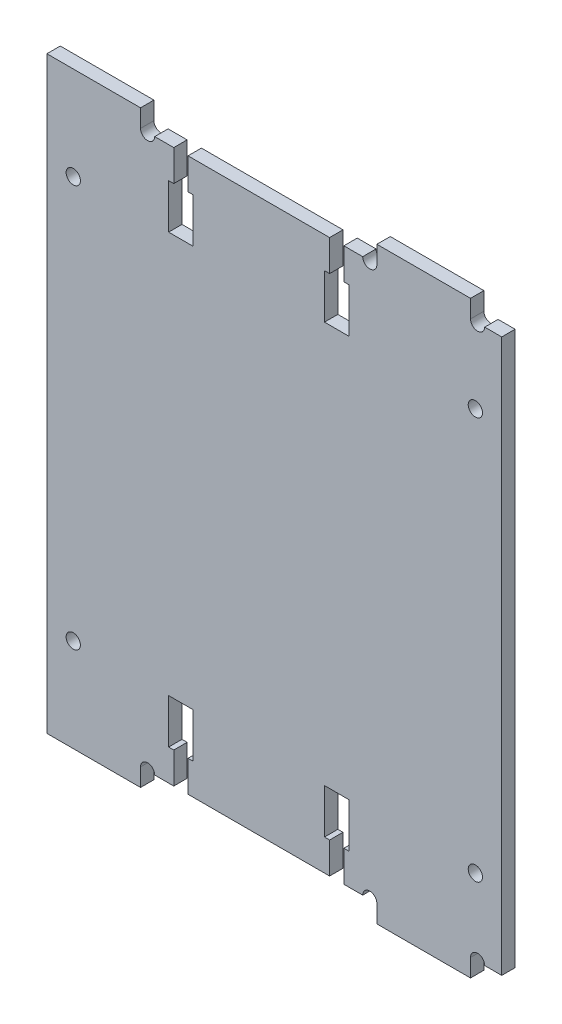
SolidWorks part; units mm, degrees
ref_plane "Front Plane" through (0, 0, 0) normal (0, 0, 1) x (1, 0, 0)
ref_plane "Top Plane" through (0, 0, 0) normal (0, 1, 0) x (1, 0, 0)
ref_plane "Right Plane" through (0, 0, 0) normal (1, 0, 0) x (0, 0, -1)
sketch "Model" plane through (0, 0, 0) normal (0, 0, 1) x (1, 0, 0)
  line L4 (110, -66) -> (110, -62)
  line L5 (89, -66) -> (110, -66)
  line L6 (89, -62) -> (89, -66)
  line L7 (81.6, -62) -> (89, -62)
  line L8 (81.6, -55) -> (81.6, -62)
  line L9 (82.75, -55) -> (81.6, -55)
  line L10 (82.75, -45) -> (82.75, -55)
  line L11 (77.25, -45) -> (82.75, -45)
  line L12 (77.25, -55) -> (77.25, -45)
  line L13 (78.4, -55) -> (77.25, -55)
  line L14 (78.4, -62) -> (78.4, -55)
  line L15 (46.65, -62) -> (78.4, -62)
  line L16 (46.65, -55) -> (46.65, -62)
  line L17 (47.8, -55) -> (46.65, -55)
  line L18 (47.8, -45) -> (47.8, -55)
  line L19 (42.3, -45) -> (47.8, -45)
  line L20 (42.3, -55) -> (42.3, -45)
  line L21 (43.45, -55) -> (42.3, -55)
  line L22 (43.45, -62) -> (43.45, -55)
  line L23 (36, -62) -> (43.45, -62)
  line L24 (36, -66) -> (36, -62)
  line L25 (15, -66) -> (36, -66)
  line L26 (15, 66) -> (15, -66)
  line L27 (36, 66) -> (15, 66)
  line L28 (36, 62) -> (36, 66)
  line L29 (43.45, 62) -> (36, 62)
  line L30 (43.45, 55) -> (43.45, 62)
  line L31 (42.3, 55) -> (43.45, 55)
  line L32 (42.3, 45) -> (42.3, 55)
  line L33 (47.8, 45) -> (42.3, 45)
  line L34 (47.8, 55) -> (47.8, 45)
  line L35 (46.65, 55) -> (47.8, 55)
  line L36 (46.65, 62) -> (46.65, 55)
  line L37 (78.4, 62) -> (46.65, 62)
  line L38 (78.4, 55) -> (78.4, 62)
  line L39 (77.25, 55) -> (78.4, 55)
  line L40 (77.25, 45) -> (77.25, 55)
  line L41 (82.75, 45) -> (77.25, 45)
  line L42 (82.75, 55) -> (82.75, 45)
  line L43 (81.6, 55) -> (82.75, 55)
  line L44 (81.6, 62) -> (81.6, 55)
  line L45 (89, 62) -> (81.6, 62)
  line L46 (89, 66) -> (89, 62)
  line L47 (110, 66) -> (89, 66)
  line L48 (110, 62) -> (110, 66)
  line L49 (117, 62) -> (110, 62)
  line L50 (117, -62) -> (117, 62)
  line L51 (110, -62) -> (117, -62)
  circle A0 centre (111.085, -45.085) radius 1.6
  circle A5 centre (111.085, 45.085) radius 1.6
  circle A13 centre (20.915, 45.085) radius 1.6
  circle A17 centre (20.915, -45.085) radius 1.6
  dimension "D5" = 3.2
  dimension "D1" = 90.17
  dimension "D2" = 20.915
  dimension "D3" = 90.17
  dimension "D4" = 5.915
  dimension "D6" = 5.915
extrude "Boss-Extrude1" add sketch "Model" along normal blind 3
sketch "Sketch2" plane through (0, 0, 3) normal (0, 0, 1) x (1, 0, 0)
  line L0 (43.45, 62) -> (36, 62) construction
  line L1 (89, 62) -> (81.6, 62) construction
  line L2 (36, -62) -> (43.45, -62) construction
  line L3 (81.6, -62) -> (89, -62) construction
  line L4 (110, -62) -> (117, -62) construction
  line L5 (117, 62) -> (110, 62) construction
  circle A0 centre (37.59, 62) radius 1.59
  circle A1 centre (87.41, 62) radius 1.59
  circle A4 centre (37.59, -62) radius 1.59
  circle A7 centre (87.41, -62) radius 1.59
  circle A8 centre (111.59, -62) radius 1.59
  circle A9 centre (111.59, 62) radius 1.59
  dimension "D1" = 3.18
  dimension "D2" = 3.18
  dimension "D3" = 3.18
  dimension "D8" = 3.18
  dimension "D9" = 3.18
  dimension "D10" = 3.18
extrude "Cut-Extrude1" cut sketch "Sketch2" against normal through all
equation "\"dim\" = 3.18"
equation "\"D1@Sketch2\"=\"dim\""
equation "\"D2@Sketch2\"=\"dim\""
equation "\"D3@Sketch2\"=\"dim\""
equation "\"D8@Sketch2\"=\"dim\""
equation "\"D9@Sketch2\"=\"dim\""
equation "\"D10@Sketch2\"=\"dim\""
